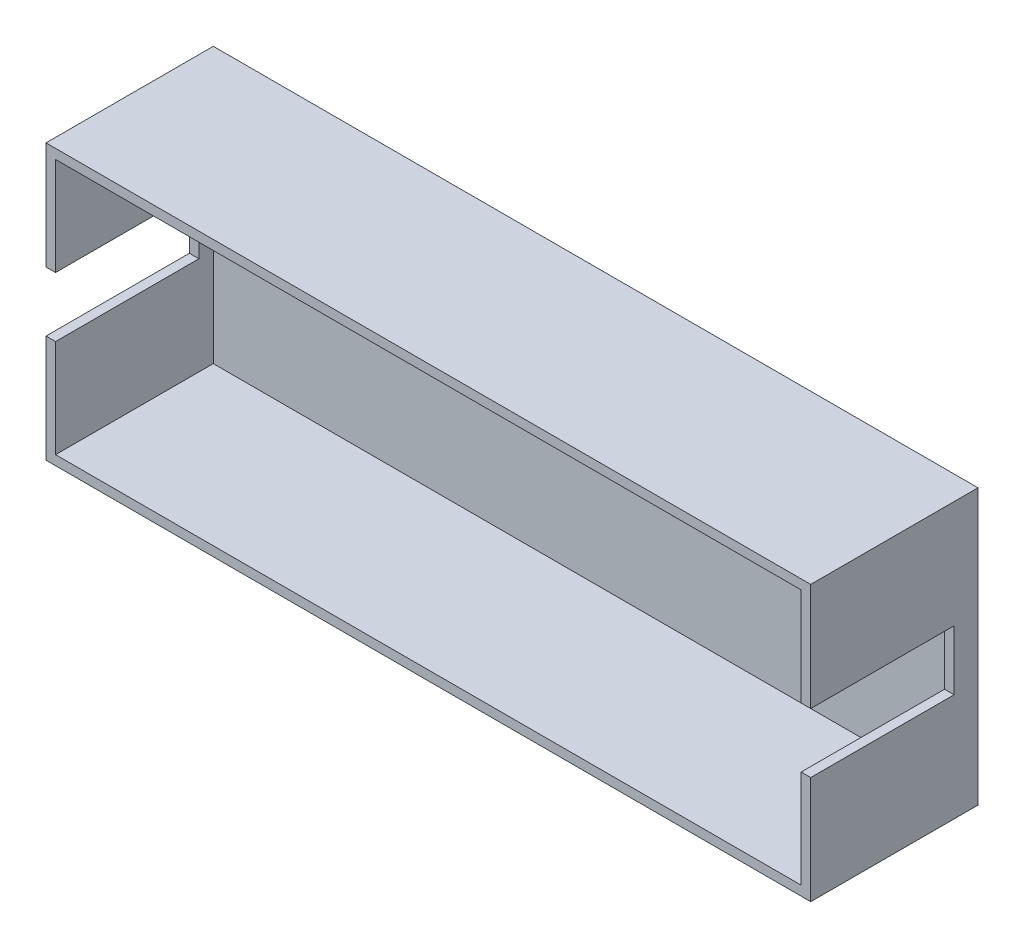
SolidWorks part; units mm, degrees
ref_plane "Front Plane" through (0, 0, 0) normal (0, 0, 1) x (1, 0, 0)
ref_plane "Top Plane" through (0, 0, 0) normal (0, 1, 0) x (1, 0, 0)
ref_plane "Right Plane" through (0, 0, 0) normal (1, 0, 0) x (0, 0, -1)
sketch "Sketch2" plane through (0, 0, 0) normal (0, 0, 1) x (1, 0, 0)
  line L1 (-32, 11.5) -> (32, 11.5)
  line L2 (-32, 11.5) -> (-32, -11.5)
  line L3 (-32, -11.5) -> (32, -11.5)
  line L4 (32, 11.5) -> (32, -11.5)
  line L5 (-32, 11.5) -> (32, -11.5) construction
  line L6 (-32, -11.5) -> (32, 11.5) construction
  point P0 (0, 0)
  dimension "D1" = 23
  dimension "D2" = 64
extrude "Boss-Extrude1" add sketch "Sketch2" along normal blind 14
sketch "Sketch3" plane through (0, 0, 14) normal (0, 0, 1) x (1, 0, 0)
  line L0 (32, 11.5) -> (-32, 11.5) construction
  line L1 (-31.2, 10.7) -> (31.2, 10.7)
  line L2 (-31.2, 10.7) -> (-31.2, -10.7)
  line L3 (-31.2, -10.7) -> (31.2, -10.7)
  line L4 (31.2, 10.7) -> (31.2, -10.7)
  line L5 (-31.2, 10.7) -> (31.2, -10.7) construction
  line L6 (-31.2, -10.7) -> (31.2, 10.7) construction
  line L7 (32, -11.5) -> (32, 11.5) construction
  point P0 (0, 0)
  dimension "D1" = 0.8
  dimension "D2" = 0.8
extrude "Cut-Extrude1" cut sketch "Sketch3" against normal blind 13.2
sketch "Sketch4" plane through (32, 0, 0) normal (1, 0, 0) x (0, 0, -1)
  line L0 (-14, -11.5) -> (-14, 11.5) construction
  line L1 (-26, 2.5) -> (-2, 2.5)
  line L2 (-26, 2.5) -> (-26, -2.5)
  line L3 (-26, -2.5) -> (-2, -2.5)
  line L4 (-2, 2.5) -> (-2, -2.5)
  line L5 (-26, 2.5) -> (-2, -2.5) construction
  line L6 (-26, -2.5) -> (-2, 2.5) construction
  point P0 (-14, 0)
  dimension "D1" = 5
  dimension "D2" = 12
extrude "Cut-Extrude3" cut sketch "Sketch4" against normal through all
